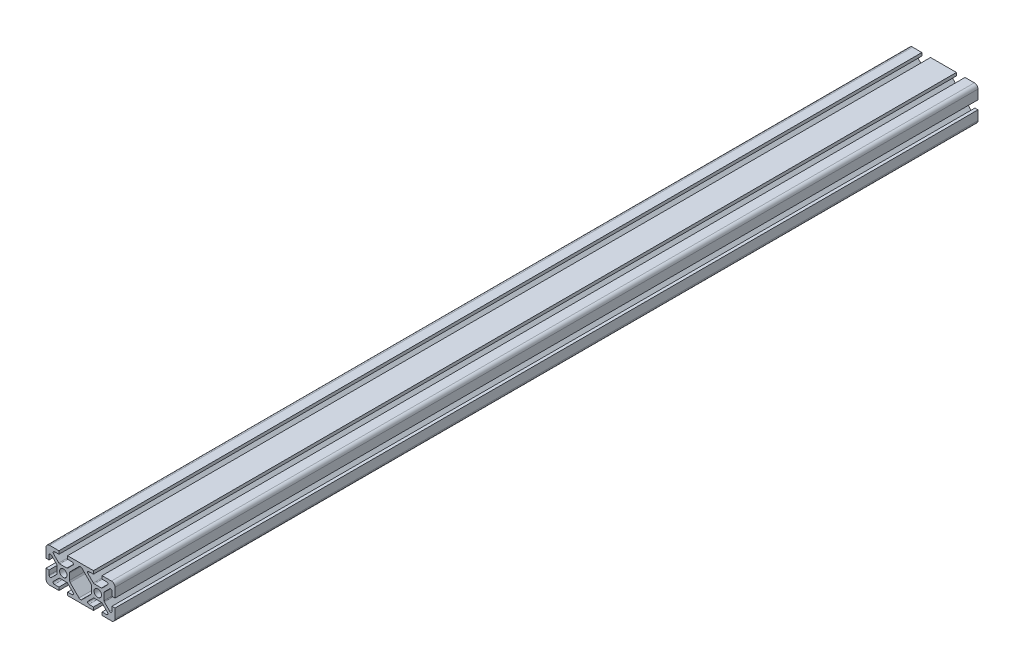
SolidWorks part; units mm, degrees
material "6063-T6"
ref_plane "Front Plane" through (0, 0, 0) normal (0, 0, 1) x (1, 0, 0)
ref_plane "Top Plane" through (0, 0, 0) normal (0, 1, 0) x (1, 0, 0)
ref_plane "Right Plane" through (0, 0, 0) normal (1, 0, 0) x (0, 0, -1)
sketch "Sketch1" plane through (0, 0, 0) normal (0, 0, 1) x (1, 0, 0)
  line L0 (10, 10) -> (10, -10) construction
  line L1 (-20, 0) -> (20, 0) construction
  line L2 (12.5, -10) -> (20, -10)
  line L3 (20, -10) -> (20, -2.5)
  line L4 (12.5, -10) -> (12.5, -8.2134)
  line L5 (12.5, -8.2134) -> (16.95, -8.2134)
  line L6 (16.95, -8.2134) -> (12.3366, -3.6)
  line L7 (10, 0) -> (20, -10) construction
  line L8 (20, -2.5) -> (18.2134, -2.5)
  line L9 (18.2134, -2.5) -> (18.2134, -6.95)
  line L10 (18.2134, -6.95) -> (13.6, -2.3366)
  line L11 (15.9067, -4.6433) -> (14.6433, -5.9067) construction
  line L12 (0, 10) -> (0, -10) construction
  line L13 (0, -10) -> (-20, -10) construction
  line L14 (-10, 10) -> (10, 10) construction
  line L15 (20, 2.5) -> (20, -2.5) construction
  circle A0 centre (10, 0) radius 2.15
  arc A1 (15.5015, -8.2134) -> (15.9257, -7.1891) centre (15.5015, -7.6134) ccw construction
  point P8 (10, -3.6)
  point P16 (15.275, -5.275)
  point P30 (20, 0)
  dimension "Center Hole Diameter" = 4.3
  dimension "D3" = 0.6
  dimension "Rail Width" = 20
  dimension "T-Slot Width" = 5
  dimension "Slot Depth" = 6.4
  dimension "Rail Height" = 40
  dimension "Inner Slot Width" = 13.9
  dimension "Hole Spacing" = 20
sketch "Sketch2" plane through (0, 0, 0) normal (1, 0, 0) x (0, 0, -1)
  line L0 (-250, -10) -> (250, -10) construction
  line L1 (-210, 0) -> (210, 0) construction
  point P6 (-210, 0)
  point P8 (210, 0)
  dimension "Length" = 500
  dimension "D1" = 40
sketch "Sketch3" plane through (0, 0, 0) normal (0, 0, 1) x (1, 0, 0)
  line L0 (12.5, -10) -> (17.9, -10)
  line L1 (12.5, -10) -> (20, -10) construction
  line L2 (12.5, -10) -> (12.5, -8.2134) construction
  line L3 (12.5, -8.2134) -> (16.95, -8.2134) construction
  line L4 (12.5, -8.2134) -> (12.5, -10)
  line L5 (12.5, -8.2134) -> (16.95, -8.2134)
  line L6 (10, -3.6) -> (12.3366, -3.6)
  line L7 (16.95, -8.2134) -> (12.3366, -3.6) construction
  line L8 (12.3366, -3.6) -> (16.95, -8.2134)
  line L9 (20, -10) -> (20, -2.5) construction
  line L10 (18.2134, -6.95) -> (13.6, -2.3366) construction
  line L11 (18.2134, -2.5) -> (18.2134, -6.95) construction
  line L12 (18.2134, -6.95) -> (18.2134, -2.5)
  line L13 (20, -2.5) -> (18.2134, -2.5) construction
  line L14 (18.2134, -2.5) -> (20, -2.5)
  line L15 (20, -2.5) -> (20, -7.9)
  line L16 (18.2134, -6.95) -> (13.6, -2.3366)
  line L17 (13.6, 0) -> (13.6, -2.3366)
  line L18 (-20, 0) -> (20, 0) construction
  line L19 (10, -3.6) -> (10, -2.15)
  line L20 (10, 10) -> (10, -10) construction
  line L21 (13.6, 0) -> (12.15, 0)
  arc A5 (17.9, -10) -> (20, -7.9) centre (17.9, -7.9) ccw
  circle A10 centre (10, 0) radius 2.15 construction
  arc A11 (10, -2.15) -> (12.15, 0) centre (10, 0) ccw
  dimension "D1" = 2.1
extrude "Boss-Extrude1" add sketch "Sketch3" along normal mid plane 500
sketch "Sketch4" plane through (0, 0, 0) normal (0, 0, 1) x (1, 0, 0)
  line L0 (10, -3.6) -> (7.6634, -3.6)
  line L4 (7.6634, -3.6) -> (3.05, -8.2134)
  line L5 (3.05, -8.2134) -> (7.5, -8.2134)
  line L6 (7.5, -8.2134) -> (7.5, -10)
  line L18 (7.5, -10) -> (0, -10)
  line L19 (12.5, -10) -> (12.5, -8.2134) construction
  line L20 (12.5, -8.2134) -> (16.95, -8.2134) construction
  line L21 (10, -3.6) -> (12.3366, -3.6) construction
  line L22 (16.95, -8.2134) -> (12.3366, -3.6) construction
  line L23 (0, -8.7366) -> (6.4, -2.3366)
  line L24 (0, 10) -> (0, -10) construction
  line L25 (6.4, -2.3366) -> (6.4, 0)
  line L26 (-20, 0) -> (20, 0) construction
  line L27 (6.4, 0) -> (7.85, 0)
  line L28 (13.6, 0) -> (12.15, 0) construction
  line L29 (0, -8.7366) -> (0, -10)
  line L30 (10, -2.15) -> (10, -3.6)
  circle A4 centre (10, 0) radius 2.15 construction
  arc A5 (7.85, 0) -> (10, -2.15) centre (10, 0) ccw
extrude "Boss-Extrude2" add sketch "Sketch4" along normal mid plane 500
mirror "Mirror1" about plane through (0, 0, 0) normal (1, 0, 0) of bodies 137 134
mirror "Mirror2" about plane through (0, 0, 0) normal (0, 1, 0) of bodies 135
fillet "Fillet1" radius 0.75 24 edges at (-7.6634, -3.6, 0) (-12.3366, -3.6, 0) (12.3366, -3.6, 0) (7.6634, -3.6, 0) (-3.05, -8.2134, 0) (-18.2134, -6.95, 0) (-16.95, -8.2134, 0) (-13.6, -2.3366, 0) (-18.2134, 6.95, 0) (-16.95, 8.2134, 0) (-12.3366, 3.6, 0) (-7.6634, 3.6, 0) (-13.6, 2.3366, 0) (-3.05, 8.2134, 0) (3.05, 8.2134, 0) (13.6, -2.3366, 0) (18.2134, 6.95, 0) (13.6, 2.3366, 0) (7.6634, 3.6, 0) (12.3366, 3.6, 0) (16.95, 8.2134, 0) (18.2134, -6.95, 0) (16.95, -8.2134, 0) (3.05, -8.2134, 0)
fillet "Fillet2" radius 1.25 6 edges at (0, -8.7366, 0) (-6.4, -2.3366, 0) (-6.4, 2.3366, 0) (6.4, -2.3366, 0) (6.4, 2.3366, 0) (0, 8.7366, 0)
equation "\"D1@Sketch3\" = \"D3@Sketch1\" * 3.5"
equation "\"D1@Boss-Extrude1\" = \"Length@Sketch2\""
equation "\"D1@Boss-Extrude2\" = \"Length@Sketch2\""
equation "\"D1@Sketch2\"=\"Rail Height@Sketch1\""
